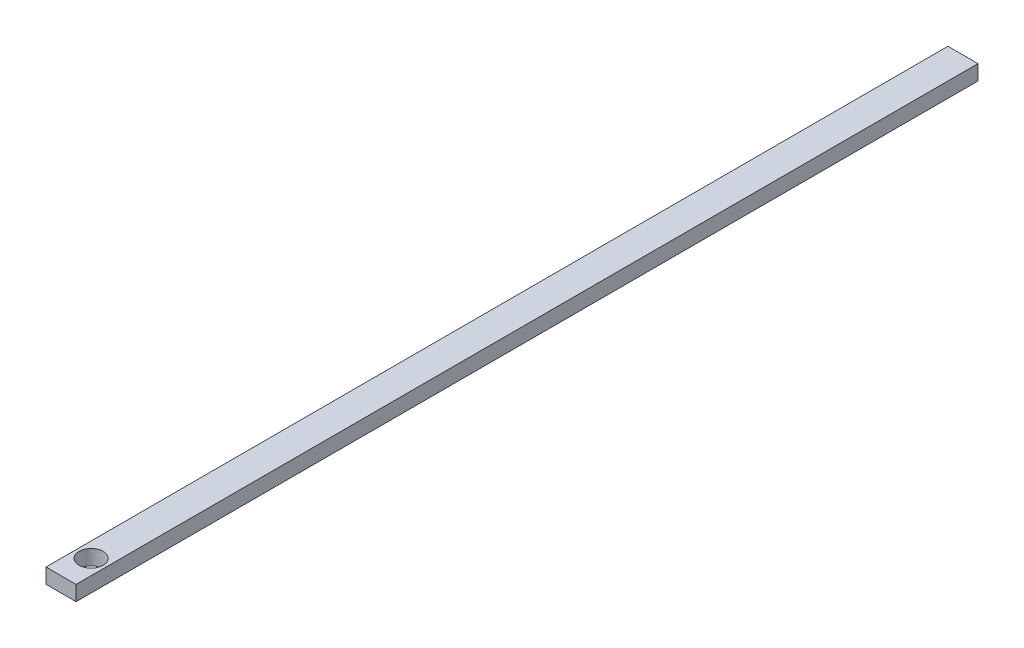
SolidWorks part; units mm, degrees
material "Gray Cast Iron"
ref_plane "Front Plane" through (0, 0, 0) normal (0, 0, 1) x (1, 0, 0)
ref_plane "Top Plane" through (0, 0, 0) normal (0, 1, 0) x (1, 0, 0)
ref_plane "Right Plane" through (0, 0, 0) normal (1, 0, 0) x (0, 0, -1)
sketch "Sketch1" plane through (0, 0, 0) normal (1, 0, 0) x (0, 0, -1)
  line L1 (-150, -2.5) -> (150, -2.5)
  line L2 (-150, -2.5) -> (-150, 2.5)
  line L3 (-150, 2.5) -> (150, 2.5)
  line L4 (150, -2.5) -> (150, 2.5)
  line L5 (-150, -2.5) -> (150, 2.5) construction
  line L6 (-150, 2.5) -> (150, -2.5) construction
  point P0 (0, 0)
  dimension "D1" = 5
  dimension "D2" = 300
extrude "Boss-Extrude1" add sketch "Sketch1" along normal blind 10 contours L3 L4 L1 L2
sketch "Sketch2" plane through (0, 2.5, 0) normal (0, 1, 0) x (1, 0, 0)
  line L0 (10, -150) -> (0, -150) construction
  line L2 (0, -150) -> (0, 150) construction
  circle A0 centre (5, -140) radius 4
  point P6 (9.2236, -143.4915)
  point P7 (0, 0)
  point P10 (0, 0)
  dimension "D1" = 10
  dimension "D2" = 5
extrude "Cut-Extrude1" cut sketch "Sketch2" against normal through all
